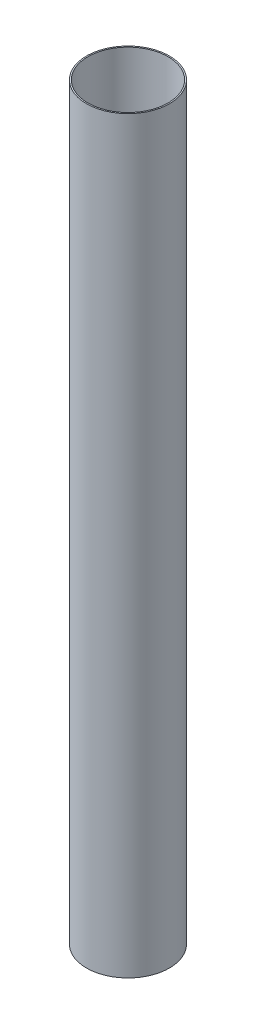
SolidWorks part; units mm, degrees
material "E-Glass Fiber"
ref_plane "Front Plane" through (0, 0, 0) normal (0, 0, 1) x (1, 0, 0)
ref_plane "Top Plane" through (0, 0, 0) normal (0, 1, 0) x (1, 0, 0)
ref_plane "Right Plane" through (0, 0, 0) normal (1, 0, 0) x (0, 0, -1)
sketch "Sketch1" plane through (0, 0, 0) normal (0, 1, 0) x (1, 0, 0)
  circle A0 centre (0, 0) radius 39.37
  circle A1 centre (0, 0) radius 38.1
  dimension "D1" = 78.74
  dimension "D2" = 76.2
extrude "Tube Extrusion" add sketch "Sketch1" along normal blind 711.2
